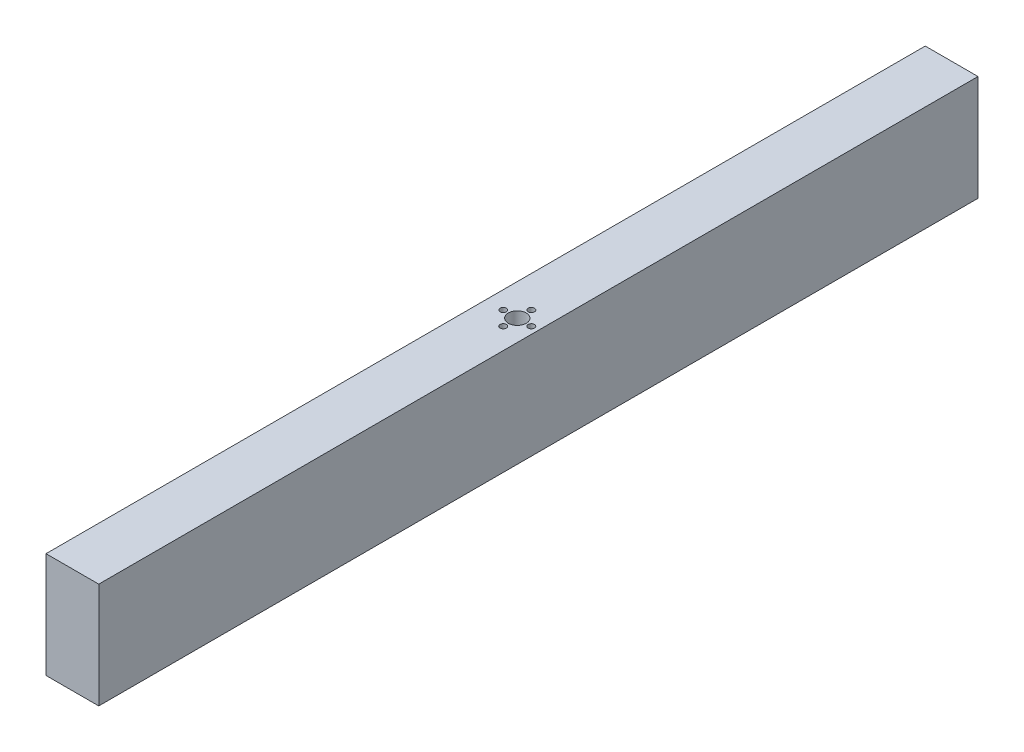
SolidWorks part; units mm, degrees
ref_plane "Front Plane" through (0, 0, 0) normal (0, 0, 1) x (1, 0, 0)
ref_plane "Top Plane" through (0, 0, 0) normal (0, 1, 0) x (1, 0, 0)
ref_plane "Right Plane" through (0, 0, 0) normal (1, 0, 0) x (0, 0, -1)
sketch "Sketch1" plane through (0, 0, 0) normal (0, 0, 1) x (1, 0, 0)
  line L1 (-15, -30) -> (15, -30)
  line L2 (-15, -30) -> (-15, 30)
  line L3 (-15, 30) -> (15, 30)
  line L4 (15, -30) -> (15, 30)
  line L5 (-15, -30) -> (15, 30) construction
  line L6 (-15, 30) -> (15, -30) construction
  point P0 (0, 0)
  dimension "D1" = 60
  dimension "D2" = 30
extrude "Boss-Extrude1" add sketch "Sketch1" along normal mid plane 500
sketch "Sketch3" plane through (0, -30, 0) normal (0, -1, 0) x (1, 0, 0)
  line L0 (15, 0) -> (-15, 0) construction
  line L1 (15, 250) -> (15, -250) construction
  line L2 (-15, 250) -> (-15, -250) construction
  circle A0 centre (3, 0) radius 4.5
  circle A1 centre (11, 0) radius 1.8
  circle A2 centre (3, -8) radius 1.8
  circle A3 centre (-5, 0) radius 1.8
  circle A4 centre (3, 8) radius 1.8
  point P10 (3, 0)
  point P11 (0, 0)
  point P19 (3, 0)
  dimension "D1" = 18
  dimension "D2" = 9
  dimension "D3" = 3.6
  dimension "D5" = 16
  dimension "D4" = 4
extrude "Cut-Extrude1" cut sketch "Sketch3" against normal through all
sketch "Sketch4" plane through (0, -30, 0) normal (0, -1, 0) x (1, 0, 0)
  line L0 (3, 0) -> (11, 0) construction
  circle A0 centre (3, 0) radius 5.1
  point P6 (3, 0)
  point P15 (3, 0)
  dimension "D1" = 10.2
extrude "Cut-Extrude2" cut sketch "Sketch4" against normal blind 10
mirror "Mirror1" about plane through (0, 0, 0) normal (0, 1, 0) of "Cut-Extrude2"
